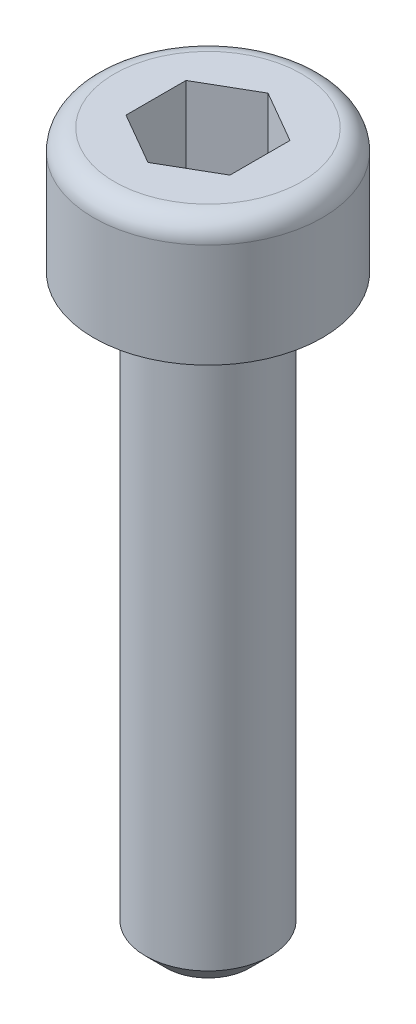
SolidWorks part; units mm, degrees
material "acero"
ref_plane "Alzado" through (0, 0, 0) normal (0, 0, 1) x (1, 0, 0)
ref_plane "Planta" through (0, 0, 0) normal (0, 1, 0) x (1, 0, 0)
ref_plane "Vista lateral" through (0, 0, 0) normal (1, 0, 0) x (0, 0, -1)
sketch "Croquis1" plane through (0, 0, 0) normal (0, 0, 1) x (1, 0, 0)
  line L0 (0, 0) -> (0, -60.9498) construction
  line L1 (0, 0) -> (2.75, 0)
  line L2 (2.75, 0) -> (2.75, -3)
  line L3 (2.75, -3) -> (1.5, -3)
  line L4 (1.5, -3) -> (1.5, -17)
  line L5 (1.5, -17) -> (0, -17)
  line L6 (0, -17) -> (0, 0)
  dimension "D1" = 14
  dimension "D2" = 3
  dimension "D3" = 5.5
  dimension "D4" = 3
revolve "Revolución1" add sketch "Croquis1" angle 360 about L0
sketch "Croquis2" plane through (0, 0, 0) normal (0, 1, 0) x (1, 0, 0)
  line L1 (1.25, 0.7217) -> (0, 1.4434)
  line L2 (0, 1.4434) -> (-1.25, 0.7217)
  line L3 (-1.25, 0.7217) -> (-1.25, -0.7217)
  line L4 (-1.25, -0.7217) -> (0, -1.4434)
  line L5 (0, -1.4434) -> (1.25, -0.7217)
  line L6 (1.25, -0.7217) -> (1.25, 0.7217)
  circle A0 centre (0, 0) radius 1.25 construction
  dimension "D1" = 2.5
extrude "Cortar-Extruir1" cut sketch "Croquis2" against normal blind 2
chamfer "Chaflán1" distance 0.5 angle 45 1 edges at (0, -17, 1.5)
fillet "Redondeo1" radius 0.5 1 edges at (0, 0, 2.75)
